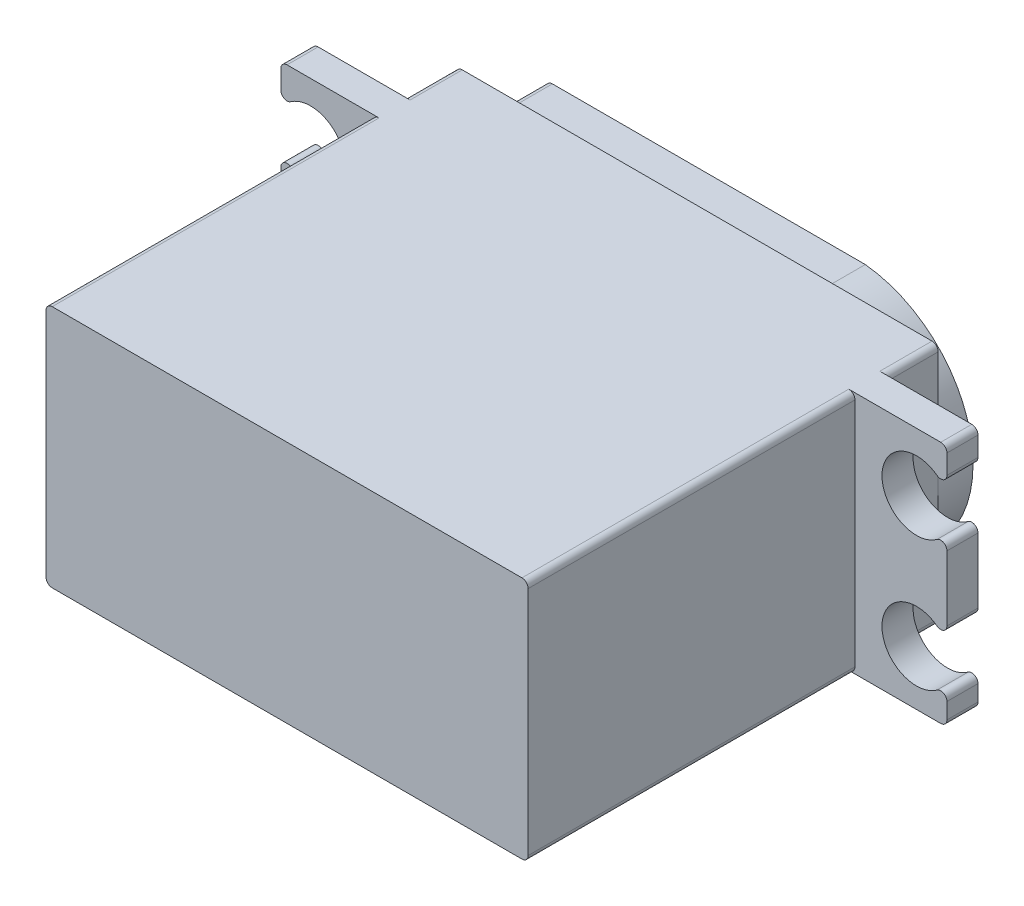
SolidWorks part; units mm, degrees
material "Ferro fundido maleável"
ref_plane "Plano frontal" through (0, 0, 0) normal (0, 0, 1) x (1, 0, 0)
ref_plane "Plano superior" through (0, 0, 0) normal (0, 1, 0) x (1, 0, 0)
ref_plane "Plano direito" through (0, 0, 0) normal (1, 0, 0) x (0, 0, -1)
sketch "Esboço1" plane through (0, 0, 0) normal (0, 1, 0) x (1, 0, 0)
  line L0 (9.7, 12.3) -> (17.1, 12.3)
  line L1 (-29.1, -16.5) -> (9.7, -16.5)
  line L3 (-29.1, 16.5) -> (9.7, 16.5)
  line L4 (9.7, -16.5) -> (9.7, 9.8)
  line L5 (-9.7, -16.5) -> (9.7, 16.5) construction
  line L6 (-9.7, 16.5) -> (9.7, -16.5) construction
  line L7 (17.1, 12.3) -> (17.1, 9.8)
  line L8 (17.1, 9.8) -> (9.7, 9.8)
  line L9 (9.7, 12.3) -> (9.7, 16.5)
  line L10 (-9.7, 16.5) -> (-29.1, -16.5) construction
  line L11 (-9.7, -16.5) -> (-29.1, 16.5) construction
  line L12 (-29.1, 12.3) -> (-29.1, 16.5)
  line L13 (-36.5, 9.8) -> (-29.1, 9.8)
  line L14 (-36.5, 12.3) -> (-36.5, 9.8)
  line L15 (-29.1, -16.5) -> (-29.1, 9.8)
  line L16 (-29.1, 12.3) -> (-36.5, 12.3)
  point P0 (0, 0)
  point P16 (-19.4, 0)
  dimension "D1" = 33
  dimension "D2" = 38.8
  dimension "D3" = 7.4
  dimension "D4" = 2.5
  dimension "D5" = 4.2
extrude "Extrusão1" add sketch "Esboço1" along normal blind 19.6
sketch "Esboço2" plane through (0, 0, -16.5) normal (0, 0, -1) x (-1, 0, 0)
  line L0 (-9.7, 19.6) -> (29.1, 19.6) construction
  line L1 (24.7, 19.4) -> (-0.9811, 19.4)
  line L2 (24.7, 19.4) -> (24.7, 14.056)
  line L3 (24.7, 0.2) -> (-0.9811, 0.2)
  line L4 (-9.7, 0) -> (29.1, 0) construction
  line L5 (29.1, 19.6) -> (29.1, 0) construction
  line L6 (24.7, 6.356) -> (24.7, 0.2)
  arc A0 (-0.9811, 19.4) -> (-0.9811, 0.2) centre (0, 9.8) ccw
  arc A1 (24.7, 6.356) -> (24.7, 14.056) centre (20.9294, 10.206) ccw
  dimension "D3" = 4.4
  dimension "D5" = 9.65
  dimension "D6" = 5.3889
  dimension "D1" = 0.2
  dimension "D2" = 0.2
  dimension "D4" = 7.7
extrude "Extrusão2" add sketch "Esboço2" along normal blind 2.85
fillet "Filete1" radius 0.5 1 edges at (17.1, 0, -11.05)
fillet "Filete2" radius 0.5 1 edges at (17.1, 19.6, -11.05)
fillet "Filete3" radius 0.5 1 edges at (-36.5, 0, -11.05)
fillet "Filete4" radius 0.5 1 edges at (-36.5, 19.6, -11.05)
fillet "Filete5" radius 0.5 1 edges at (-24.7, 0.2, -17.925)
fillet "Filete6" radius 0.5 1 edges at (-24.7, 19.4, -17.925)
fillet "Filete7" radius 0.5 1 edges at (-29.1, 0, 3.35)
fillet "Filete8" radius 0.5 1 edges at (-29.1, 19.6, 3.35)
fillet "Filete9" radius 0.5 1 edges at (9.7, 19.6, 3.35)
fillet "Filete10" radius 0.5 1 edges at (9.7, 0, 3.35)
fillet "Filete11" radius 0.5 1 edges at (-29.1, 0, -14.4)
fillet "Filete12" radius 0.5 1 edges at (-29.1, 19.6, -14.4)
fillet "Filete13" radius 0.5 1 edges at (9.7, 19.6, -14.4)
fillet "Filete14" radius 0.5 1 edges at (9.7, 0, -14.4)
sketch "Esboço3" plane through (0, 0, -19.35) normal (0, 0, -1) x (-1, 0, 0)
  circle A0 centre (0.0514, 9.9666) radius 6.5
  dimension "D1" = 13
extrude "Extrusão3" add sketch "Esboço3" along normal blind 2
sketch "Esboço4" plane through (0, 0, -21.35) normal (0, 0, -1) x (-1, 0, 0)
  circle A0 centre (0, 9.8) radius 4.45
extrude "Extrusão4" cut sketch "Esboço4" against normal blind 22
sketch "Esboço5" plane through (0, 0, -12.3) normal (0, 0, -1) x (-1, 0, 0)
  circle A0 centre (-14.6506, 14.9089) radius 2.7766
  circle A1 centre (-14.6506, 4.4134) radius 2.7766
  circle A2 centre (34.1061, 14.9089) radius 2.7766
  circle A3 centre (34.1061, 4.4134) radius 2.7766
extrude "Extrusão6" cut sketch "Esboço5" against normal blind 10
fillet "Filete15" radius 0.5 1 edges at (17.1, 5.721, -11.05)
fillet "Filete16" radius 0.5 1 edges at (17.1, 3.1059, -11.05)
fillet "Filete17" radius 0.5 1 edges at (17.1, 16.2165, -11.05)
fillet "Filete18" radius 0.5 1 edges at (17.1, 13.6013, -11.05)
fillet "Filete19" radius 0.5 1 edges at (-36.5, 16.3156, -11.05)
fillet "Filete20" radius 0.5 1 edges at (-36.5, 13.5022, -11.05)
fillet "Filete21" radius 0.5 1 edges at (-36.5, 3.0068, -11.05)
fillet "Filete22" radius 0.5 1 edges at (-36.5, 5.8201, -11.05)
